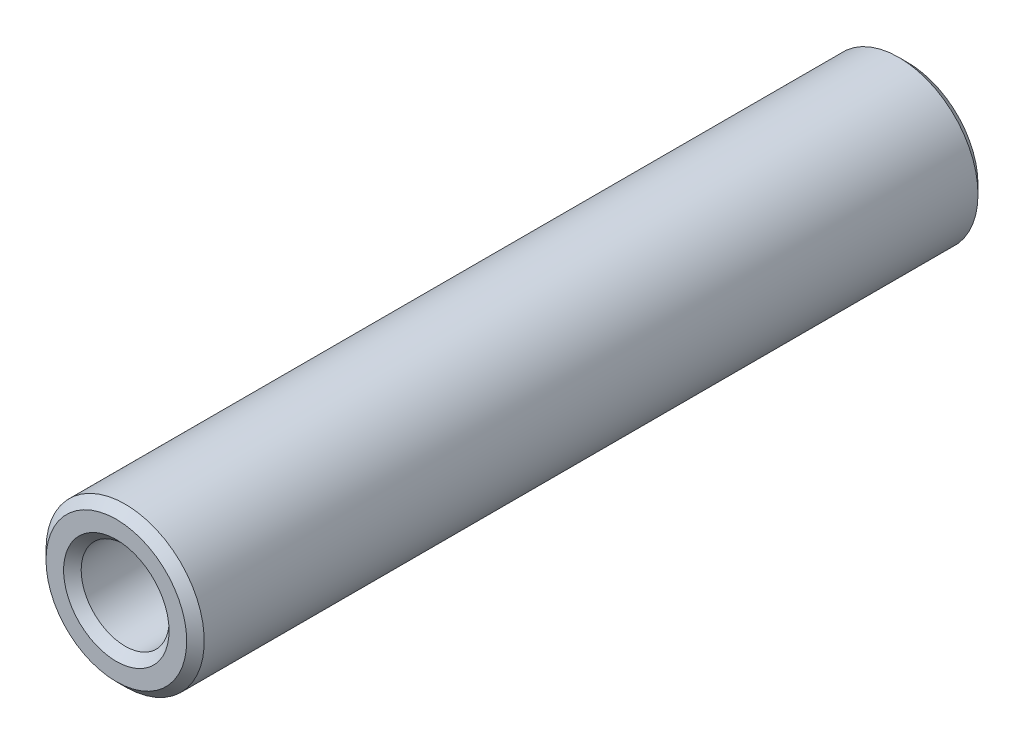
SolidWorks part; units mm, degrees
ref_plane "Front Plane" through (0, 0, 0) normal (0, 0, 1) x (1, 0, 0)
ref_plane "Top Plane" through (0, 0, 0) normal (0, 1, 0) x (1, 0, 0)
ref_plane "Right Plane" through (0, 0, 0) normal (1, 0, 0) x (0, 0, -1)
sketch "Sketch1" plane through (0, 0, 0) normal (0, 0, 1) x (1, 0, 0)
  circle A0 centre (0, 0) radius 2.5
  circle A1 centre (0, 0) radius 4.5
  dimension "D1" = 5
  dimension "D2" = 2
extrude "Boss-Extrude1" add sketch "Sketch1" along normal mid plane 45
chamfer "Chamfer1" distance 0.5 angle 45 4 edges at (2.5, 0, -22.5) (4.5, 0, -22.5) (2.5, 0, 22.5) (4.5, 0, 22.5)
